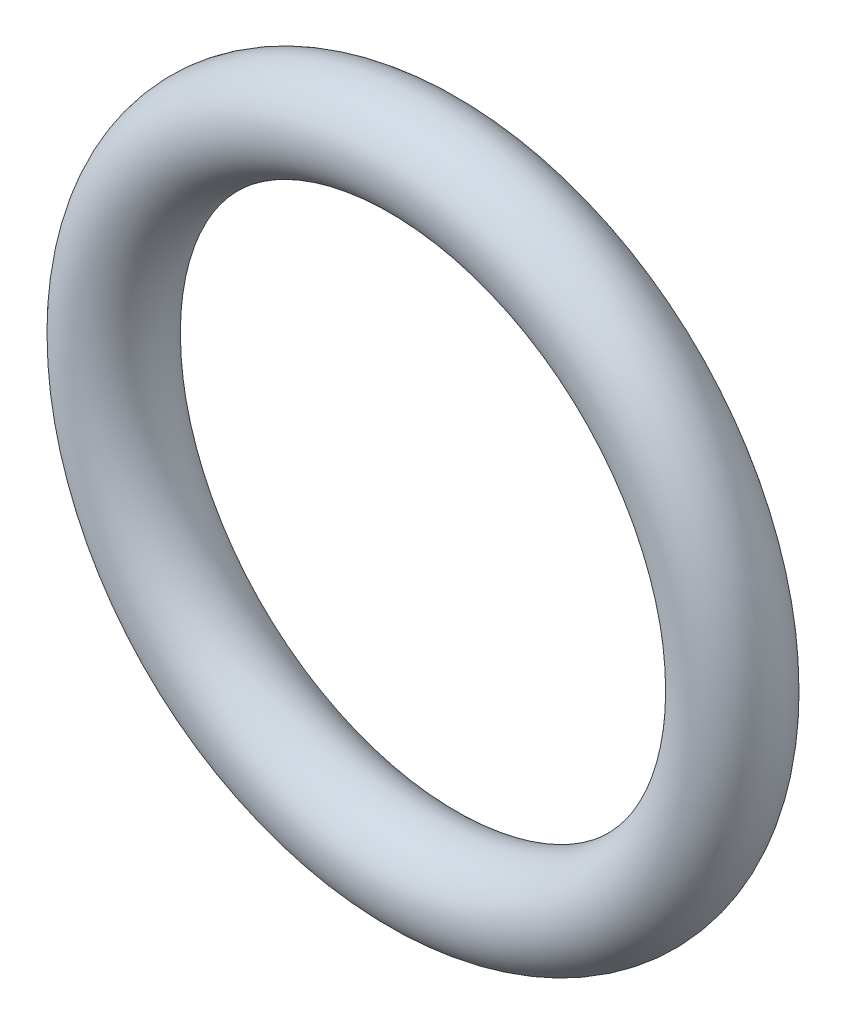
SolidWorks part; units mm, degrees
ref_plane "前视基准面" through (0, 0, 0) normal (0, 0, 1) x (1, 0, 0)
ref_plane "上视基准面" through (0, 0, 0) normal (0, 1, 0) x (1, 0, 0)
ref_plane "右视基准面" through (0, 0, 0) normal (1, 0, 0) x (0, 0, -1)
other "Configuration Table"
sketch "Sk_oring10" plane through (0, 0, 0) normal (0, 1, 0) x (1, 0, 0)
  line L0 (0, 0) -> (0, -2) construction
  circle A0 centre (5.9, 0) radius 0.9
revolve "Rev_oring10" add sketch "Sk_oring10" angle 360 about L0
